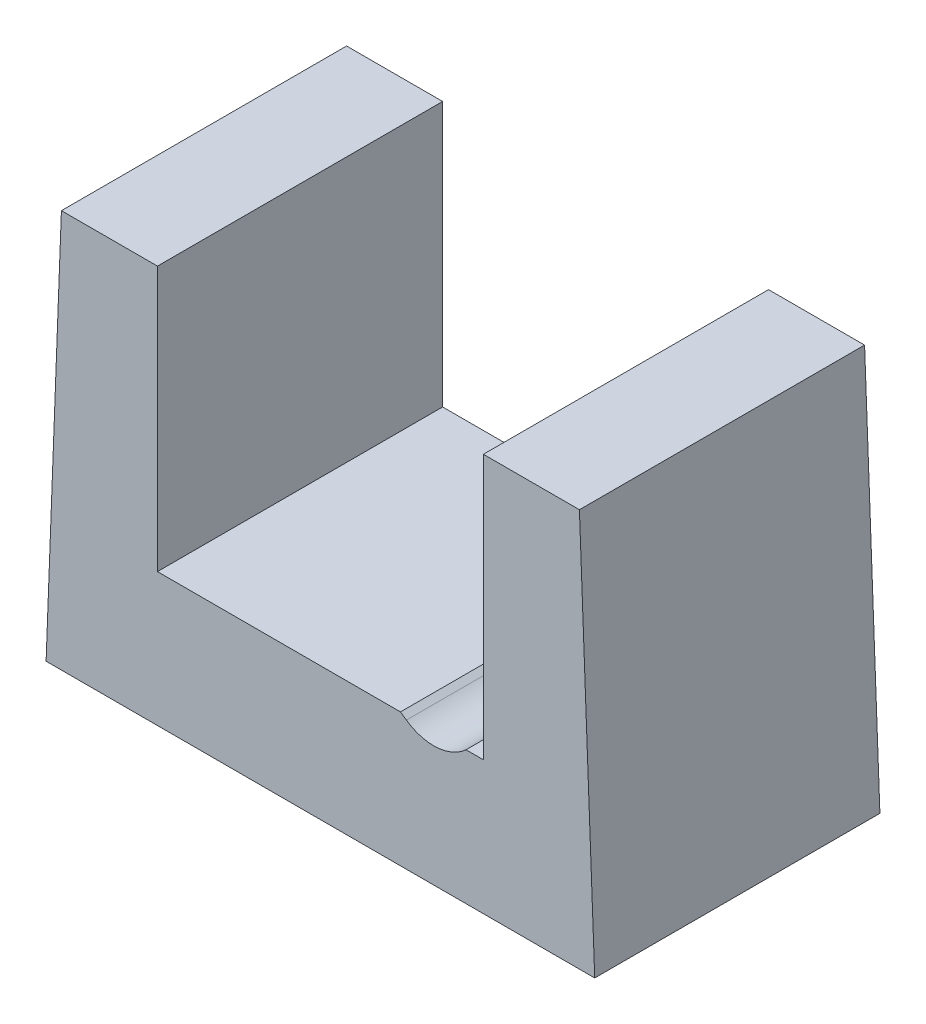
SolidWorks part; units mm, degrees
material "Foam"
ref_plane "Front Plane" through (0, 0, 0) normal (0, 0, 1) x (1, 0, 0)
ref_plane "Top Plane" through (0, 0, 0) normal (0, 1, 0) x (1, 0, 0)
ref_plane "Right Plane" through (0, 0, 0) normal (1, 0, 0) x (0, 0, -1)
sketch "Sketch1" plane through (0, 0, 0) normal (0, 0, 1) x (1, 0, 0)
  line L0 (-11.1, 83.4741) -> (-9.1, 83.4741) construction
  line L1 (0, 41.6741) -> (20.2, 41.6741) construction
  line L2 (20.2, 41.6741) -> (20.2, 83.4741) construction
  line L3 (0, 83.4741) -> (9.1, 83.4741)
  line L4 (10.1, 83.4741) -> (10.1, 41.6741) construction
  line L5 (0, 62.5741) -> (20.2, 62.5741) construction
  line L6 (-20.2, 83.4741) -> (-20.2, 41.6741) construction
  line L7 (-20.2, 41.6741) -> (0, 41.6741) construction
  line L8 (-20.2, 83.4741) -> (-11.1, 83.4741)
  line L9 (-10.1, 83.4741) -> (-10.1, 41.6741) construction
  line L10 (-20.2, 62.5741) -> (0, 62.5741) construction
  line L11 (-20.2, 41.6741) -> (-17.9755, -0.9384) construction
  line L12 (20.2, 41.6741) -> (17.9755, -0.9384) construction
  line L13 (0, 0) -> (0, 147.6909) construction
  line L14 (-20.2, 90.8741) -> (-17.9867, 148.3831)
  line L15 (20.2, 90.8741) -> (17.9867, 148.3831)
  line L16 (11.1, 83.4741) -> (20.2, 83.4741)
  line L17 (-11.1, 83.4741) -> (-11.1, 89.4741)
  line L18 (-11.1, 89.4741) -> (-9.1, 89.4741)
  line L19 (-9.1, 83.4741) -> (-9.1, 89.4741)
  line L20 (11.1, 83.4741) -> (9.1, 83.4741) construction
  line L21 (11.1, 83.4741) -> (11.1, 89.4741)
  line L22 (11.1, 89.4741) -> (9.1, 89.4741)
  line L23 (9.1, 83.4741) -> (9.1, 89.4741)
  line L24 (-9.1, 83.4741) -> (0, 83.4741)
  line L25 (-20.2, 90.8741) -> (20.2, 90.8741) construction
  line L26 (-20.2, 83.4741) -> (-20.2, 90.8741)
  line L27 (20.2, 83.4741) -> (20.2, 90.8741)
  circle A0 centre (10.1, 73.3741) radius 6.5 construction
  arc A1 (-17.9755, -0.9384) -> (17.9755, -0.9384) centre (0, 0) cw construction
  circle A2 centre (0, 0) radius 2.5 construction
  arc A3 (-17.9755, -0.9384) -> (17.9755, -0.9384) centre (0, 0) ccw construction
  circle A4 centre (5.2, 88.1241) radius 1.5
  circle A5 centre (15, 88.1241) radius 1.5
  circle A6 centre (-10.1, 51.7741) radius 6.5 construction
  circle A7 centre (-15, 88.1241) radius 1.5
  circle A8 centre (-5.2, 88.1241) radius 1.5
  circle A9 centre (-15, 37.0241) radius 1.5 construction
  circle A10 centre (-5.2, 37.0241) radius 1.5 construction
  circle A11 centre (0, 0) radius 52.75 construction
  circle A12 centre (5.2, 37.0241) radius 1.5 construction
  circle A13 centre (15, 37.0241) radius 1.5 construction
  arc A14 (17.9867, 148.3831) -> (-17.9867, 148.3831) centre (0, 147.6909) ccw
  circle A15 centre (0, 147.6909) radius 3.95
  circle A16 centre (10.1, 73.3741) radius 75 construction
  dimension "D1" = 5
  dimension "D2" = 18
  dimension "D10" = 51.1
  dimension "D3" = 13
  dimension "D4" = 3
  dimension "D8" = 9.8
  dimension "D9" = 105.5
  dimension "D5" = 20.2
  dimension "D19" = 36
  dimension "D20" = 7.9
  dimension "D18" = 150
  dimension "D6" = 10.1
  dimension "D7" = 41.8
  dimension "D13" = 10.1
  dimension "D14" = 6
  dimension "D15" = 9.8
  dimension "D16" = 2
  dimension "D21" = 7.4
extrude "Main Body Link B1" add sketch "Sketch1" along normal blind 21
sketch "Sketch2" plane through (0, 0, 21) normal (0, 0, 1) x (1, 0, 0)
  line L0 (0, 147.6909) -> (0, 83.4741) construction
  line L1 (-12, 134.2745) -> (12, 134.2745) construction
  line L2 (-12, 134.2745) -> (-12, 123.585)
  line L3 (-12, 100.6909) -> (3.2782, 100.6909)
  line L4 (12, 128.1722) -> (12, 106.7932)
  line L5 (-12, 117.4827) -> (12, 117.4827) construction
  line L6 (-12, 111.3804) -> (-12, 100.6909)
  line L7 (12, 100.6909) -> (-12, 117.4827) construction
  line L8 (-12, 117.4827) -> (12, 134.2745) construction
  line L9 (3.2782, 100.6909) -> (-12, 111.3804)
  line L10 (-12, 123.585) -> (-2.9299, 129.9309)
  line L12 (-3.2782, 117.4827) -> (12, 106.7932)
  line L13 (-3.2782, 117.4827) -> (12, 128.1722)
  line L14 (3.2782, 100.6909) -> (12, 100.6909) construction
  line L15 (12, 100.6909) -> (12, 106.7932) construction
  line L16 (-12, 123.585) -> (-12, 117.4827) construction
  line L17 (-12, 117.4827) -> (-12, 111.3804) construction
  line L19 (12, 134.2745) -> (12, 128.1722) construction
  line L20 (-9.1, 83.4741) -> (9.1, 83.4741) construction
  arc A0 (-12, 134.2745) -> (-2.9299, 129.9309) centre (0, 147.6909) ccw
  arc A1 (-17.9867, 148.3831) -> (-12, 134.2745) centre (0, 147.6909) ccw construction
  arc A2 (12, 134.2745) -> (17.9867, 148.3831) centre (0, 147.6909) ccw construction
  arc A3 (17.9867, 148.3831) -> (-17.9867, 148.3831) centre (0, 147.6909) ccw construction
  dimension "D1" = 24
  dimension "D2" = 47
  dimension "D3" = 10
extrude "Cut-Extrude1" cut sketch "Sketch2" against normal up to next contours L13 L12 L4 | A0 L2 L10 | L6 L3 L9
sketch "Sketch3" plane through (0, 0, 21) normal (0, 0, 1) x (1, 0, 0)
  line L0 (-3.9526, 111.8523) -> (8.3378, 103.2531) construction
  line L1 (3.2782, 100.6909) -> (-12, 111.3804) construction
  line L2 (-3.2782, 117.4827) -> (12, 106.7932) construction
  line L3 (3.2782, 100.6909) -> (-12, 111.3804) construction
  line L4 (-3.2782, 117.4827) -> (12, 106.7932) construction
  line L5 (-4.3609, 106.0356) -> (1.3718, 114.2293) construction
  line L6 (-5.9591, 108.9845) -> (6.3314, 100.3854)
  line L7 (-1.9462, 114.72) -> (10.3443, 106.1209)
  arc A0 (-1.9462, 114.72) -> (-5.9591, 108.9845) centre (-3.9526, 111.8523) ccw
  arc A1 (6.3314, 100.3854) -> (10.3443, 106.1209) centre (8.3378, 103.2531) ccw
  dimension "D1" = 7
  dimension "D2" = 3
  dimension "D3" = 12
extrude "PulleyIdler" cut sketch "Sketch3" along direction (0, 0, 1) on the side against the normal up to next (21 mm away)
fillet "Fillet1" radius 1 9 edges at (-12, 100.6909, 10.5) (3.2782, 100.6909, 10.5) (-12, 111.3804, 10.5) (12, 106.7932, 10.5) (12, 128.1722, 10.5) (-3.2782, 117.4827, 10.5) (-12, 123.585, 10.5) (-2.9299, 129.9309, 10.5) (-12, 134.2745, 10.5)
sketch "Sketch4" plane through (0, 0, 21) normal (0, 0, 1) x (1, 0, 0)
  line L0 (-17.9867, 148.3831) -> (-20.2, 90.8741) construction
  line L1 (-20.2, 83.4741) -> (20.2, 83.4741)
  line L2 (-20.2, 83.4741) -> (-20.2, 90.8741)
  line L3 (-20.2, 90.8741) -> (20.2, 90.8741)
  line L4 (20.2, 83.4741) -> (20.2, 90.8741)
  line L5 (-19.0723, 120.1741) -> (19.0723, 120.1741)
  line L6 (-19.0723, 120.1741) -> (-19.0723, 165.6909)
  line L7 (-19.0723, 165.6909) -> (19.0723, 165.6909)
  line L8 (19.0723, 120.1741) -> (19.0723, 165.6909)
  line L9 (20.2, 90.8741) -> (17.9867, 148.3831) construction
  arc A0 (17.9867, 148.3831) -> (-17.9867, 148.3831) centre (0, 147.6909) ccw construction
  dimension "D1" = 7.4
  dimension "D2" = 29.3
extrude "Cut-Extrude2" cut sketch "Sketch4" against normal through all
sketch "Sketch5" plane through (0, 0, 21) normal (0, 0, 1) x (1, 0, 0)
  line L0 (-12, 100.6909) -> (5.8947, 100.6909)
  line L1 (-5.9591, 108.9845) -> (6.3314, 100.3854) construction
  line L2 (-11, 100.6909) -> (0.1045, 100.6909) construction
  line L3 (-12, 100.6909) -> (-12, 120.1741)
  line L4 (-19.0723, 120.1741) -> (0.5685, 120.1741) construction
  line L5 (-12, 120.1741) -> (12, 120.1741)
  line L6 (12, 120.1741) -> (12, 100.6909)
  line L7 (12, 100.6909) -> (10.7221, 100.6909)
  line L8 (-12, 109.4603) -> (-12, 101.6909) construction
  line L9 (5.8947, 100.6909) -> (6.3314, 100.3854)
  arc A0 (6.3314, 100.3854) -> (10.3443, 106.1209) centre (8.3378, 103.2531) ccw construction
  arc A1 (6.3314, 100.3854) -> (10.7221, 100.6909) centre (8.3378, 103.2531) ccw
extrude "Cut-Extrude4" cut sketch "Sketch5" against normal through all
equation "\"D20@Sketch1\"=8-\"radii_fit@Parameters@Parameters.SLDPRT\""
equation "\"D18@Sketch1\"=\"CenterDist3@Parameters@Parameters.SLDPRT\"*2"
equation "\"D9@Sketch1\"=\"CenterDist2@Parameters@Parameters.SLDPRT\"*2"
